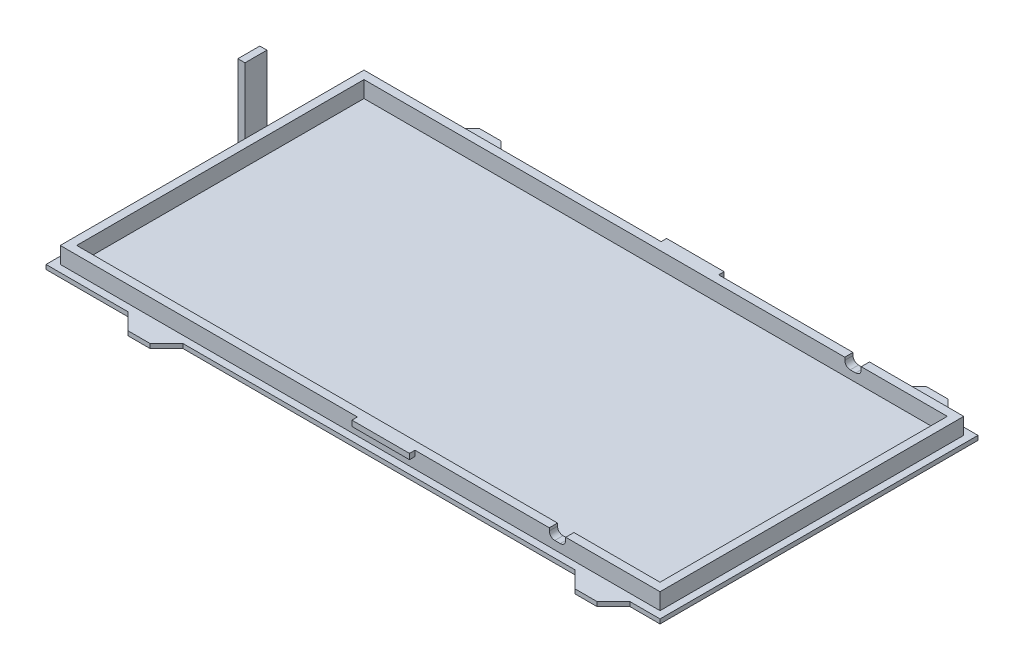
SolidWorks part; units mm, degrees
ref_plane "Front Plane" through (0, 0, 0) normal (0, 0, 1) x (1, 0, 0)
ref_plane "Top Plane" through (0, 0, 0) normal (0, 1, 0) x (1, 0, 0)
ref_plane "Right Plane" through (0, 0, 0) normal (1, 0, 0) x (0, 0, -1)
sketch "Sketch1" plane through (0, 0, 0) normal (0, 1, 0) x (1, 0, 0)
  line L1 (-56, 29) -> (56, 29)
  line L2 (-56, 29) -> (-56, -29)
  line L3 (-56, -29) -> (56, -29)
  line L4 (56, 29) -> (56, -29)
  line L5 (-56, 29) -> (56, -29) construction
  line L6 (-56, -29) -> (56, 29) construction
  point P0 (0, 0)
  dimension "D1" = 112
  dimension "D2" = 58
extrude "Boss-Extrude1" add sketch "Sketch1" along normal blind 0.8
sketch "Sketch2" plane through (0, 0.8, 0) normal (0, 1, 0) x (1, 0, 0)
  line L1 (-56, 29) -> (56, 29)
  line L2 (-56, 29) -> (-56, -29)
  line L3 (-56, -29) -> (56, -29)
  line L4 (56, 29) -> (56, -29)
  line L5 (-56, 29) -> (56, -29) construction
  line L6 (-56, -29) -> (56, 29) construction
  line L7 (-55, 28) -> (55, 28)
  line L8 (-55, 28) -> (-55, -28)
  line L9 (-55, -28) -> (55, -28)
  line L10 (55, 28) -> (55, -28)
  line L11 (-55, 28) -> (55, -28) construction
  line L12 (-55, -28) -> (55, 28) construction
  point P0 (0, 0)
  point P7 (0, 0)
  dimension "D1" = 1
  dimension "D2" = 1
extrude "Boss-Extrude2" add sketch "Sketch2" along normal blind 28
sketch "Sketch3" plane through (0, 0.8, 0) normal (0, 1, 0) x (1, 0, 0)
  line L0 (55, 28) -> (-55, 28) construction
  line L1 (-55, -28) -> (55, -28) construction
  line L3 (-55, -28) -> (55, -28) construction
  line L4 (55, -28) -> (55, 28) construction
  circle A0 centre (-36, 25.5) radius 1.75
  circle A1 centre (-36, -25.5) radius 1.75
  circle A2 centre (45.5, 25.5) radius 1.75
  circle A3 centre (45.5, -25.5) radius 1.75
  dimension "D1" = 2.5
  dimension "D2" = 3.5
  dimension "D3" = 3.5
  dimension "D4" = 2.5
  dimension "D5" = 81.5
  dimension "D6" = 81.5
  dimension "D7" = 3.5
  dimension "D8" = 3.5
  dimension "D9" = 2.5
  dimension "D10" = 2.5
  dimension "D11" = 9.5
  dimension "D12" = 9.5
extrude "Cut-Extrude1" cut sketch "Sketch3" against normal blind 28
sketch "Sketch4" plane through (0, 0.8, 0) normal (0, 1, 0) x (1, 0, 0)
  circle A0 centre (-36, 25.5) radius 3.25
  circle A1 centre (45.5, 25.5) radius 3.25
  circle A2 centre (-36, -25.5) radius 3.25
  circle A3 centre (45.5, -25.5) radius 3.25
  circle A4 centre (-36, 25.5) radius 1.75 construction
  circle A5 centre (45.5, 25.5) radius 1.75 construction
  circle A6 centre (-36, -25.5) radius 1.75 construction
  circle A7 centre (45.5, -25.5) radius 1.75 construction
  circle A8 centre (-36, 25.5) radius 1.75
  circle A9 centre (45.5, 25.5) radius 1.75
  circle A10 centre (45.5, -25.5) radius 1.75
  circle A11 centre (-36, -25.5) radius 1.75
  dimension "D1" = 1.5
  dimension "D2" = 1.5
  dimension "D3" = 1.5
  dimension "D4" = 1.5
extrude "Boss-Extrude3" add sketch "Sketch4" along normal blind 2
sketch "Sketch5" plane through (-55, 0, 0) normal (1, 0, 0) x (0, 0, -1)
  line L0 (28, 0.8) -> (-28, 0.8) construction
  line L1 (-28, 28.8) -> (-28, 0.8) construction
  line L2 (28, 28.8) -> (-28, 28.8) construction
  line L4 (-10.5, 10.8) -> (-10.5, 28.8)
  line L5 (-10.5, 28.8) -> (-5.5, 28.8)
  line L6 (-5.5, 10.8) -> (-5.5, 28.8)
  arc A0 (-10.5, 10.8) -> (-5.5, 10.8) centre (-8, 10.8) ccw
  dimension "D1" = 5
  dimension "D2" = 10
  dimension "D3" = 20
  dimension "D4" = 2.5
extrude "Cut-Extrude2" cut sketch "Sketch5" against normal blind 2
sketch "Sketch6" plane through (0, 0, 29) normal (0, 0, 1) x (1, 0, 0)
  line L0 (-56, 28.8) -> (56, 28.8) construction
  line L1 (56, 28.8) -> (56, 0) construction
  line L4 (34.5, 25.8) -> (34.5, 28.8)
  line L5 (34.5, 28.8) -> (37.5, 28.8)
  line L6 (37.5, 25.8) -> (37.5, 28.8)
  arc A0 (34.5, 25.8) -> (37.5, 25.8) centre (36, 25.8) ccw
  dimension "D1" = 3
  dimension "D2" = 3
  dimension "D3" = 20
extrude "Cut-Extrude3" cut sketch "Sketch6" against normal blind 72
sketch "Sketch7" plane through (0, 0, 0) normal (0, -1, 0) x (1, 0, 0)
  line L0 (-41, 29) -> (-38, 32)
  line L1 (-56, 29) -> (56, 29) construction
  line L2 (-38, 32) -> (-34, 32)
  line L3 (-34, 32) -> (-31, 29)
  line L4 (-31, 29) -> (-41, 29)
  line L5 (40.5, 29) -> (43.5, 32)
  line L6 (43.5, 32) -> (47.5, 32)
  line L7 (47.5, 32) -> (50.5, 29)
  line L8 (50.5, 29) -> (40.5, 29)
  line L9 (-41, -29) -> (-38, -32)
  line L10 (56, -29) -> (-56, -29) construction
  line L11 (-38, -32) -> (-34, -32)
  line L12 (-34, -32) -> (-31, -29)
  line L13 (-31, -29) -> (-41, -29)
  line L14 (40.5, -29) -> (43.5, -32)
  line L15 (43.5, -32) -> (47.5, -32)
  line L16 (47.5, -32) -> (50.5, -29)
  line L17 (50.5, -29) -> (40.5, -29)
  circle A0 centre (-36, 25.5) radius 1.75 construction
  circle A1 centre (45.5, 25.5) radius 1.75 construction
  circle A2 centre (-36, -25.5) radius 1.75 construction
  dimension "D1" = 5
  dimension "D2" = 5
  dimension "D3" = 3
  dimension "D4" = 45
  dimension "D5" = 5
  dimension "D6" = 5
  dimension "D7" = 5
  dimension "D8" = 5
  dimension "D9" = 3
  dimension "D10" = 45
extrude "Boss-Extrude4" add sketch "Sketch7" against normal blind 28.8
sketch "Sketch8" plane through (0, 0, 29) normal (0, 0, 1) x (1, 0, 0)
  line L0 (-31, 28.8) -> (34.5, 28.8) construction
  line L1 (-1, 27.3) -> (10.5, 27.3)
  line L2 (-1, 27.3) -> (-1, 25.8)
  line L3 (-1, 25.8) -> (10.5, 25.8)
  line L4 (10.5, 27.3) -> (10.5, 25.8)
  line L5 (-1, 27.3) -> (10.5, 25.8) construction
  line L6 (-1, 25.8) -> (10.5, 27.3) construction
  line L7 (-31, 28.8) -> (-31, 0) construction
  line L8 (40.5, 28.8) -> (40.5, 0) construction
  point P0 (4.75, 26.55)
  dimension "D1" = 1.5
  dimension "D2" = 1.5
  dimension "D3" = 30
  dimension "D4" = 30
extrude "Cut-Extrude4" cut sketch "Sketch8" against normal blind 70
sketch "Sketch9" plane through (0, 0, 29) normal (0, 0, 1) x (1, 0, 0)
  line L0 (56, 28.8) -> (56, 0) construction
  line L1 (-56, 28.8) -> (56, 28.8)
  line L2 (-56, 28.8) -> (-56, 0.8)
  line L3 (-56, 0.8) -> (56, 0.8)
  line L4 (56, 28.8) -> (56, 0.8)
  line L5 (-31, 0) -> (40.5, 0) construction
  dimension "D1" = 0.8
extrude "Cut-Extrude5" cut sketch "Sketch9" against normal blind 70 and the other way blind 70
sketch "Sketch10" plane through (0, 0.8, 0) normal (0, 1, 0) x (1, 0, 0)
  line L1 (-39.5131, 27.6754) -> (-31.1851, 27.6754)
  line L2 (-39.5131, 27.6754) -> (-39.5131, 20.2303)
  line L3 (-39.5131, 20.2303) -> (-31.1851, 20.2303)
  line L4 (-31.1851, 27.6754) -> (-31.1851, 20.2303)
  line L5 (42.5549, 27.6754) -> (47.91, 27.6754)
  line L6 (42.5549, 27.6754) -> (42.5549, 21.7217)
  line L7 (42.5549, 21.7217) -> (47.91, 21.7217)
  line L8 (47.91, 27.6754) -> (47.91, 21.7217)
  line L9 (-42.596, -21.7937) -> (-31.1851, -21.7937)
  line L10 (-42.596, -21.7937) -> (-42.596, -27.5088)
  line L11 (-42.596, -27.5088) -> (-31.1851, -27.5088)
  line L12 (-31.1851, -21.7937) -> (-31.1851, -27.5088)
  line L13 (40.7104, -20.3533) -> (49.4407, -20.3533)
  line L14 (40.7104, -20.3533) -> (40.7104, -28.2113)
  line L15 (40.7104, -28.2113) -> (49.4407, -28.2113)
  line L16 (49.4407, -20.3533) -> (49.4407, -28.2113)
extrude "Boss-Extrude5" add sketch "Sketch10" against normal blind 0.8
sketch "Sketch11" plane through (0, 0.8, 0) normal (0, 1, 0) x (1, 0, 0)
  line L0 (40.5, 29) -> (-31, 29) construction
  line L1 (-54.7, 27.7) -> (54.7, 27.7)
  line L2 (-54.7, 27.7) -> (-54.7, 25.3606)
  line L3 (-53.2, 26.2) -> (53.2, 26.2)
  line L4 (54.7, 27.7) -> (54.7, 24.6844)
  line L5 (54.7, 27.7) -> (51.897, 27.7)
  line L6 (54.7, 27.7) -> (54.7, -27.7)
  line L7 (54.7, -27.7) -> (50.7954, -27.7)
  line L8 (53.2, 26.2) -> (53.2, -26.2)
  line L9 (54.7, -27.7) -> (-54.7, -27.7)
  line L10 (54.7, -27.7) -> (54.7, -25.2226)
  line L11 (53.2, -26.2) -> (-53.2, -26.2)
  line L12 (-54.7, -27.7) -> (-54.7, -24.5464)
  line L13 (-54.7, -27.7) -> (-52.8062, -27.7)
  line L14 (-54.7, -27.7) -> (-54.7, 27.7)
  line L15 (-54.7, 27.7) -> (-51.7046, 27.7)
  line L16 (-53.2, -26.2) -> (-53.2, 26.2)
  line L17 (-56, -29) -> (-56, 29) construction
  line L18 (56, -29) -> (56, 29) construction
  line L19 (-31, -29) -> (40.5, -29) construction
  dimension "D1" = 1.5
  dimension "D2" = 1.5
  dimension "D3" = 1.5
  dimension "D4" = 1.5
  dimension "D5" = 1.3
  dimension "D6" = 1.3
  dimension "D7" = 1.3
  dimension "D8" = 1.3
extrude "Boss-Extrude6" add sketch "Sketch11" along normal blind 3 contours L14 L12 L9 L7 L6 L4 L1 L2 L11 L16 L3 L8
sketch "Sketch12" plane through (0, 0, 27.7) normal (0, 0, 1) x (1, 0, 0)
  line L0 (54.7, 3.8) -> (-54.7, 3.8) construction
  line L1 (-0.5, 3.8) -> (10, 3.8)
  line L2 (-0.5, 3.8) -> (-0.5, 2.8)
  line L3 (-0.5, 2.8) -> (10, 2.8)
  line L4 (10, 3.8) -> (10, 2.8)
  line L5 (-31, 0.8) -> (-31, 0) construction
  line L6 (40.5, 0.8) -> (40.5, 0) construction
  point P8 (-31, 0.4)
  dimension "D1" = 1
  dimension "D2" = 30.5
  dimension "D3" = 30.5
extrude "Boss-Extrude7" add sketch "Sketch12" along normal blind 1
sketch "Sketch13" plane through (0, 0, -27.7) normal (0, 0, -1) x (-1, 0, 0)
  line L0 (54.7, 3.8) -> (-54.7, 3.8) construction
  line L1 (-10, 3.8) -> (0.5, 3.8)
  line L2 (-10, 3.8) -> (-10, 2.8)
  line L3 (-10, 2.8) -> (0.5, 2.8)
  line L4 (0.5, 3.8) -> (0.5, 2.8)
  line L5 (-40.5, 0.8) -> (-40.5, 0) construction
  line L6 (31, 0.8) -> (31, 0) construction
  dimension "D1" = 1
  dimension "D2" = 30.5
  dimension "D3" = 30.5
extrude "Boss-Extrude8" add sketch "Sketch13" along normal blind 1
sketch "Sketch14" plane through (0, 0.8, 0) normal (0, 1, 0) x (1, 0, 0)
  line L0 (-56, -29) -> (-56, 29) construction
  line L1 (-56, 10) -> (-54.7, 10)
  line L2 (-56, 10) -> (-56, 6)
  line L3 (-56, 6) -> (-54.7, 6)
  line L4 (-54.7, 10) -> (-54.7, 6)
  line L5 (-54.7, -27.7) -> (-54.7, 27.7) construction
  line L6 (-41, 29) -> (-56, 29) construction
  line L7 (-56, -29) -> (-41, -29) construction
  dimension "D1" = 19
  dimension "D2" = 35
extrude "Boss-Extrude9" add sketch "Sketch14" along normal blind 15
sketch "Sketch15" plane through (0, 0, 27.7) normal (0, 0, 1) x (1, 0, 0)
  line L0 (54.7, 3.8) -> (10, 3.8) construction
  line L1 (34.5, 3.8) -> (37.5, 3.8)
  line L2 (34.5, 3.8) -> (34.5, 2.3)
  line L3 (34.5, 2.3) -> (37.5, 2.3)
  line L4 (37.5, 3.8) -> (37.5, 2.3)
  line L5 (56, 0.8) -> (56, 0) construction
  dimension "D1" = 18.5
  dimension "D2" = 3
  dimension "D3" = 1.5
extrude "Cut-Extrude6" cut sketch "Sketch15" against normal blind 70
fillet "Fillet1" radius 1 4 edges at (34.5, 2.3, -26.95) (37.5, 2.3, -26.95) (37.5, 2.3, 26.95) (34.5, 2.3, 26.95)
